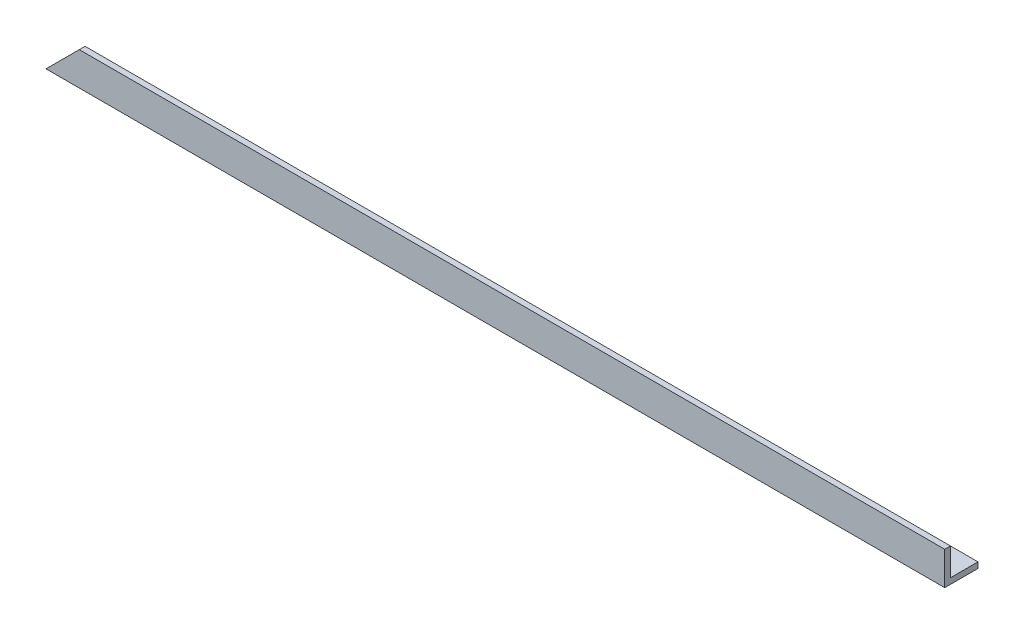
SolidWorks part; units mm, degrees
ref_plane "Front Plane" through (0, 0, 0) normal (0, 0, 1) x (1, 0, 0)
ref_plane "Top Plane" through (0, 0, 0) normal (0, 1, 0) x (1, 0, 0)
ref_plane "Right Plane" through (0, 0, 0) normal (1, 0, 0) x (0, 0, -1)
sketch "Sketch1" plane through (0, 0, 0) normal (1, 0, 0) x (0, 0, -1)
  line L0 (0, 0) -> (20, 0)
  line L1 (20, 0) -> (20, 3.4612)
  line L2 (20, 3.4612) -> (3.4612, 3.4612)
  line L3 (3.4612, 3.4612) -> (3.4612, 20)
  line L4 (3.4612, 20) -> (0, 20)
  line L5 (0, 20) -> (0, 0)
  dimension "D1" = 3.4612
  dimension "D2" = 20
extrude "Boss-Extrude1" add sketch "Sketch1" along normal blind 540
sketch "Sketch2" plane through (0, 0, 0) normal (0, 0, -1) x (1, 0, 0)
  line L11 (0, -20) -> (0, 0)
  line L15 (0, 0) -> (20, -20)
  line L16 (540, -20) -> (0, -20) construction
  line L17 (20, -20) -> (0, -20)
extrude "Cut-Extrude1" cut sketch "Sketch2" along normal through all
